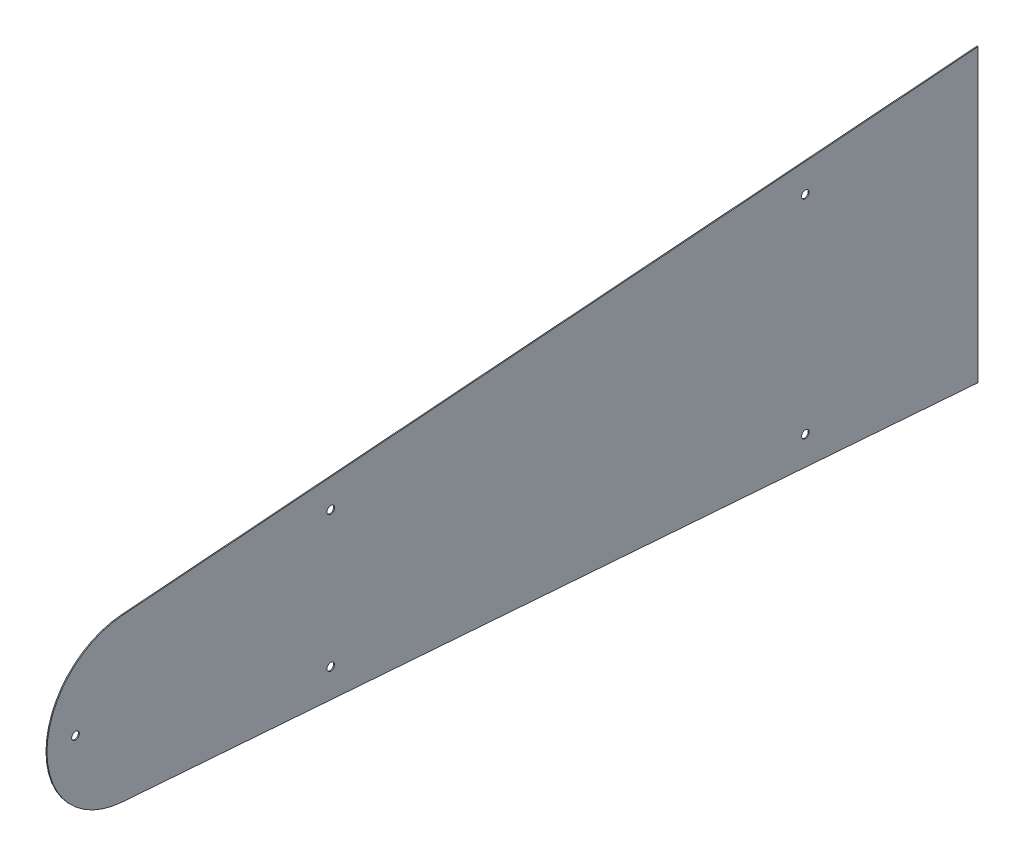
SolidWorks part; units mm, degrees
ref_plane "Front Plane" through (0, 0, 0) normal (1, 0, 0) x (0, 1, 0)
ref_plane "Top Plane" through (0, 0, 0) normal (0, 0, 1) x (0, 1, 0)
ref_plane "Right Plane" through (0, 0, 0) normal (0, 1, 0) x (-1, 0, 0)
sketch "Sketch1" plane through (0, 0, 0) normal (1, 0, 0) x (0, 1, 0)
  line L0 (-170, 0) -> (170, 0) construction
  line L1 (-170, 0) -> (-100.6925, 916.4549) construction
  line L2 (170, 0) -> (100.6925, 916.4549) construction
  line L3 (0, 0) -> (0, 908.84) construction
  line L4 (-152.8791, 15.875) -> (-84.8627, 915.2578)
  line L5 (-152.8791, 15.875) -> (152.8791, 15.875)
  line L6 (152.8791, 15.875) -> (84.8627, 915.2578)
  arc A0 (100.6925, 916.4549) -> (-100.6925, 916.4549) centre (0, 908.84) ccw construction
  arc A1 (-100.6925, 916.4549) -> (0, 807.86) centre (0, 908.84) ccw construction
  arc A2 (0, 807.86) -> (100.6925, 916.4549) centre (0, 908.84) ccw construction
  arc A3 (84.8627, 915.2578) -> (-84.8627, 915.2578) centre (0, 908.84) ccw
  point P4 (0, 0)
  dimension "D3" = 201.96
  dimension "D1" = 340
  dimension "D2" = 908.84
  dimension "D4" = 15.875
extrude "Boss-Extrude1" add sketch "Sketch1" along normal mid plane 1
sketch "Sketch2" plane through (0.5, 0, 0) normal (1, 0, 0) x (0, 1, 0)
  line L0 (-84.8627, 915.2578) -> (-152.8791, 15.875) construction
  line L1 (152.8791, 15.875) -> (84.8627, 915.2578) construction
  line L2 (-84.8627, 915.2578) -> (-152.8791, 15.875)
  line L3 (152.8791, 15.875) -> (84.8627, 915.2578)
  line L4 (152.8791, 15.875) -> (138.9942, 199.4757) construction
  line L5 (138.9942, 199.4757) -> (101.289, 698.052) construction
  line L6 (0, 908.84) -> (0, 15.875) construction
  line L7 (101.289, 698.052) -> (71.3744, 695.7897) construction
  line L8 (138.9942, 199.4757) -> (109.0796, 197.2134) construction
  line L9 (0, 993.945) -> (0, 963.945) construction
  arc A0 (84.8627, 915.2578) -> (-84.8627, 915.2578) centre (0, 908.84) ccw construction
  arc A1 (84.8627, 915.2578) -> (-84.8627, 915.2578) centre (0, 908.84) ccw
  circle A2 centre (71.3744, 695.7897) radius 4
  circle A3 centre (109.0796, 197.2134) radius 4
  circle A4 centre (0, 963.945) radius 4
  circle A5 centre (-71.3744, 695.7897) radius 4
  circle A6 centre (-109.0796, 197.2134) radius 4
  point P9 (0, 993.945)
  point P12 (-101.289, 698.052)
  point P13 (-138.9942, 199.4757)
  dimension "D4" = 8
  dimension "D5" = 8
  dimension "D1" = 184.125
  dimension "D2" = 500
  dimension "D3" = 30
  dimension "D6" = 30
extrude "Cut-Extrude1" cut sketch "Sketch2" against normal through all both and the other way through all contours A5 | A4 | A2 | A3 | A6
